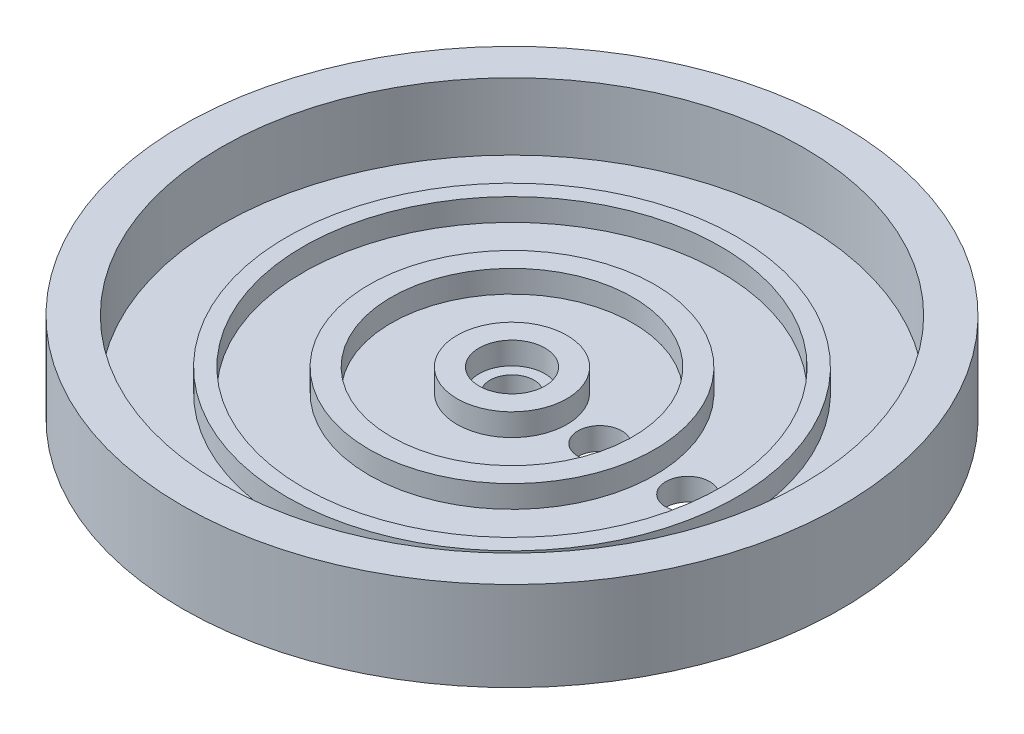
SolidWorks part; units mm, degrees
material "ABS"
ref_plane "Front Plane" through (0, 0, 0) normal (0, 0, 1) x (1, 0, 0)
ref_plane "Top Plane" through (0, 0, 0) normal (0, 1, 0) x (1, 0, 0)
ref_plane "Right Plane" through (0, 0, 0) normal (1, 0, 0) x (0, 0, -1)
sketch "Sketch2" plane through (0, 0, 0) normal (0, 1, 0) x (1, 0, 0)
  circle A0 centre (0, 0) radius 1
  circle A1 centre (4, 0) radius 1
  circle A2 centre (8, 0) radius 1
  circle A4 centre (0, 0) radius 15
  circle A6 centre (0, 0) radius 9 construction
  circle A7 centre (0, 0) radius 11 construction
  point P19 (0, 0)
  dimension "D1" = 2
  dimension "D3" = 30
  dimension "D4" = 2
  dimension "D5" = 4
  dimension "D2" = 3
extrude "Boss-Extrude2" add sketch "Sketch2" along normal blind 1.016
sketch "Sketch3" plane through (0, 1.016, 0) normal (0, 1, 0) x (1, 0, 0)
  circle A2 centre (0, 0) radius 1.5
  circle A4 centre (0, 0) radius 2.5
  circle A5 centre (0, 0) radius 5.5
  circle A6 centre (0, 0) radius 6.5
  circle A7 centre (0, 0) radius 9.5
  circle A11 centre (0, 0) radius 10.25
  circle A13 centre (0, 0) radius 13.25
  circle A14 centre (0, 0) radius 15
  circle M4 centre (0, 0) radius 15
  dimension "D1" = 3
  dimension "D2" = 3
  dimension "D3" = 3
  dimension "D4" = 1
  dimension "D5" = 5
  dimension "D7" = 3
  dimension "D8" = 20.5
extrude "Boss-Extrude4" add sketch "Sketch3" along normal blind 1.016 contours A13 M4 | A11 A7 | A6 A5 | A4 A2
sketch "Sketch5" plane through (0, 2.032, 0) normal (0, 1, 0) x (1, 0, 0)
  circle A0 centre (0, 0) radius 13.25
  circle A1 centre (0, 0) radius 15
extrude "Boss-Extrude5" add sketch "Sketch5" along normal blind 2.032
